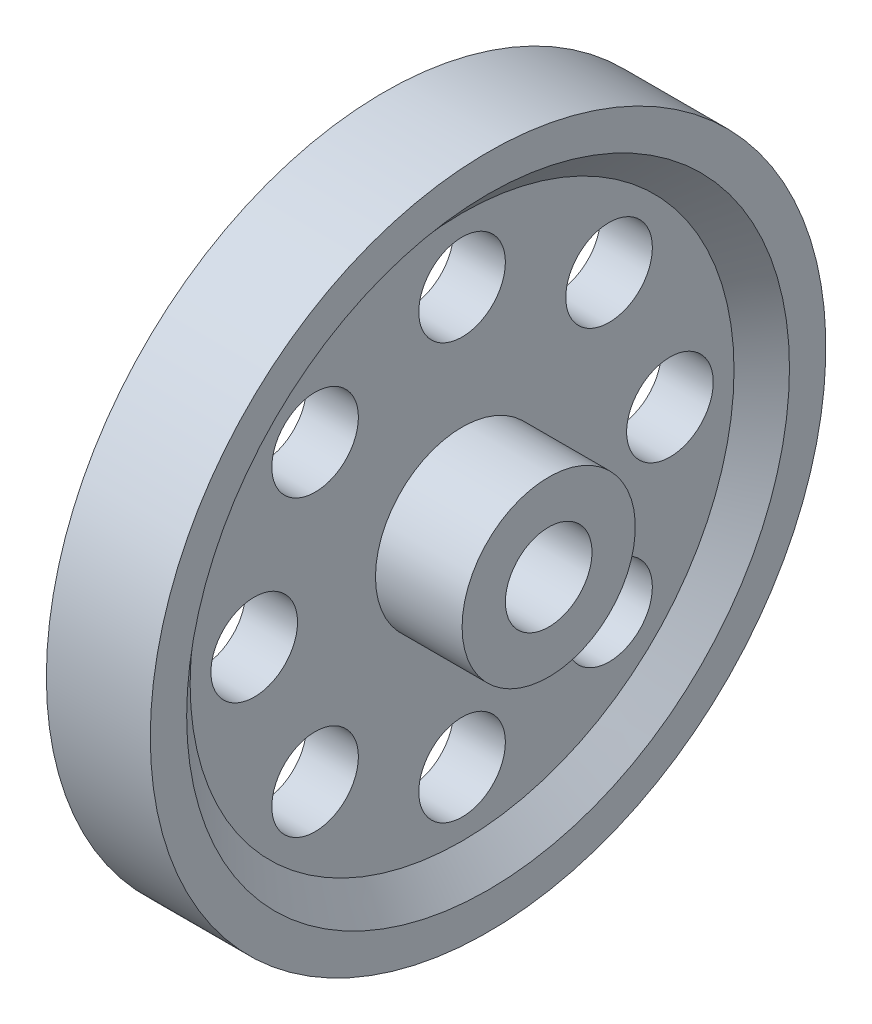
SolidWorks part; units mm, degrees
ref_plane "Front Plane" through (0, 0, 0) normal (0, 0, 1) x (1, 0, 0)
ref_plane "Top Plane" through (0, 0, 0) normal (0, 1, 0) x (1, 0, 0)
ref_plane "Right Plane" through (0, 0, 0) normal (1, 0, 0) x (0, 0, -1)
sketch "Sketch1" plane through (0, 0, 0) normal (0, 0, 1) x (1, 0, 0)
  line L0 (0, 0) -> (0, 15.7)
  line L1 (0, 15.7) -> (-1.5, 17.4)
  line L2 (-1.5, 17.4) -> (-1.5, 19.5)
  line L3 (-1.5, 19.5) -> (4.5, 19.5)
  line L4 (4.5, 19.5) -> (4.5, 17.4)
  line L5 (4.5, 17.4) -> (3, 15.7)
  line L6 (3, 15.7) -> (3, 5)
  line L7 (3, 5) -> (8, 5)
  line L8 (8, 5) -> (8, 2.5)
  line L9 (8, 2.5) -> (0, 2.5)
  line L10 (0, 0) -> (20.9672, 0) construction
  line L11 (0, 7) -> (-1, 6)
  line L12 (-1, 6) -> (-1, 2.5)
  line L13 (-1, 2.5) -> (0, 2.5)
  line L14 (4.5, 17.4) -> (-1.5, 17.4) construction
  line L15 (1.5, 19.5) -> (1.5, 0) construction
  line L16 (3, 15.7) -> (0, 15.7) construction
  point P18 (1.5, 15.7)
  dimension "D1" = 19.5
  dimension "D2" = 6
  dimension "D3" = 15.7
  dimension "D4" = 3
  dimension "D5" = 1.7
  dimension "D6" = 7
  dimension "D7" = 1
  dimension "D8" = 6
  dimension "D9" = 2.5
  dimension "D10" = 5
  dimension "D11" = 8
revolve "Revolve1" add sketch "Sketch1" angle 360 about L10
sketch "Sketch2" plane through (3, 0, 0) normal (1, 0, 0) x (0, 0, -1)
  line L0 (0, 12) -> (0, 0) construction
  circle A0 centre (0, 12) radius 2.5
  circle A1 centre (8.4853, 8.4853) radius 2.5
  circle A2 centre (12, 0) radius 2.5
  circle A3 centre (8.4853, -8.4853) radius 2.5
  circle A4 centre (0, -12) radius 2.5
  circle A5 centre (-8.4853, -8.4853) radius 2.5
  circle A6 centre (-12, 0) radius 2.5
  circle A7 centre (-8.4853, 8.4853) radius 2.5
  point P21 (0, 0)
  dimension "D1" = 5
  dimension "D2" = 12
  dimension "D3" = 8
extrude "Cut-Extrude1" cut sketch "Sketch2" against normal through all
